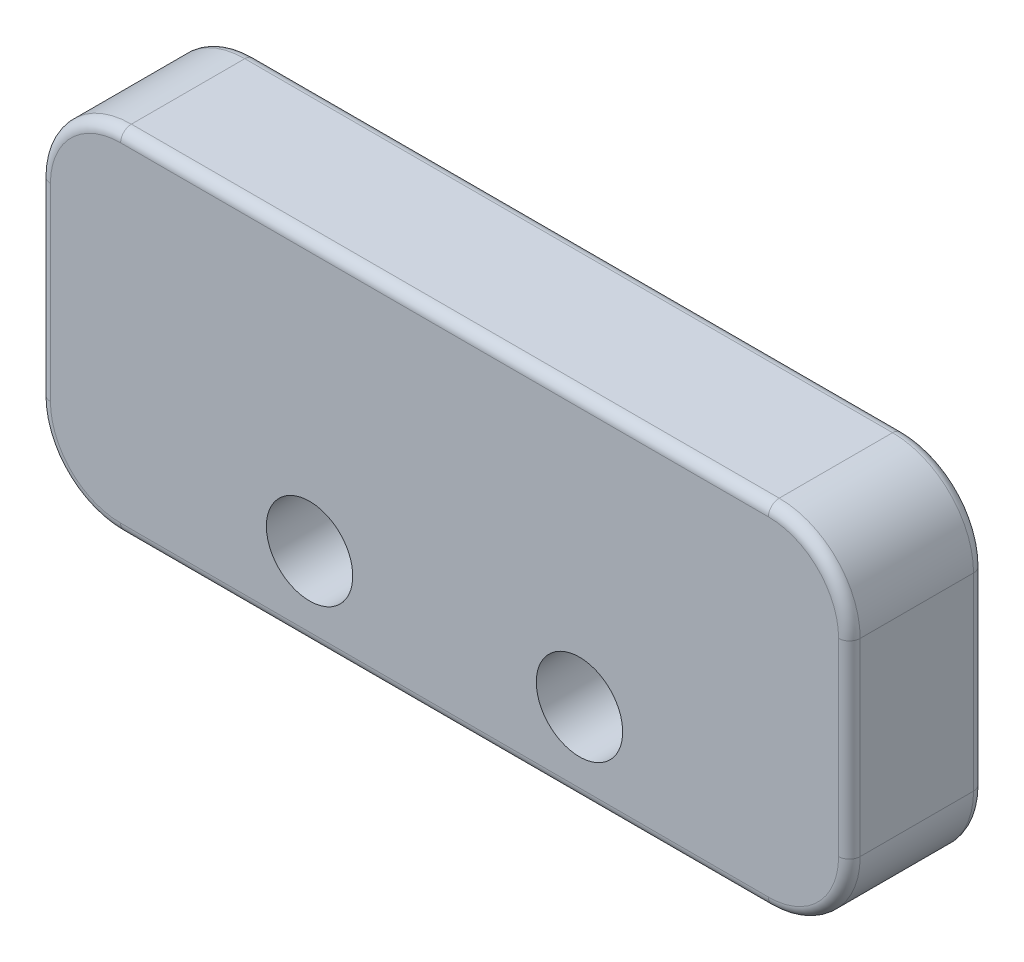
SolidWorks part; units mm, degrees
ref_plane "Front Plane" through (0, 0, 0) normal (0, 0, 1) x (1, 0, 0)
ref_plane "Top Plane" through (0, 0, 0) normal (0, 1, 0) x (1, 0, 0)
ref_plane "Right Plane" through (0, 0, 0) normal (1, 0, 0) x (0, 0, -1)
sketch "Sketch1" plane through (0, 0, 0) normal (0, 0, 1) x (1, 0, 0)
  line L1 (0, 0) -> (30, 0)
  line L2 (0, 0) -> (0, -13)
  line L3 (0, -13) -> (30, -13)
  line L4 (30, 0) -> (30, -13)
  dimension "D1" = 30
  dimension "D2" = 13
extrude "Boss-Extrude1" add sketch "Sketch1" along normal blind 5
sketch "Sketch2" plane through (0, 0, 0) normal (0, 0, -1) x (-1, 0, 0)
  line L0 (-30, 0) -> (0, 0) construction
  line L1 (-30, -13) -> (-30, 0) construction
  line L2 (0, 0) -> (0, -13) construction
  circle A0 centre (-20, -10) radius 1.6
  circle A1 centre (-10, -10) radius 1.6
  dimension "D5" = 3.2
  dimension "D6" = 3.2
  dimension "D1" = 10
  dimension "D2" = 10
  dimension "D3" = 10
  dimension "D4" = 10
extrude "Cut-Extrude1" cut sketch "Sketch2" against normal through all
fillet "Fillet1" radius 3 4 edges at (0, 0, 2.5) (0, -13, 2.5) (30, -13, 2.5) (30, 0, 2.5)
fillet "Fillet2" radius 0.4 16 edges at (29.1213, -0.8787, 5) (30, -6.5, 5) (29.1213, -12.1213, 5) (15, -13, 5) (0.8787, -12.1213, 5) (0, -6.5, 5) (0.8787, -0.8787, 5) (29.1213, -0.8787, 0) (30, -6.5, 0) (29.1213, -12.1213, 0) (15, -13, 0) (0.8787, -12.1213, 0) (0, -6.5, 0) (0.8787, -0.8787, 0) (15, 0, 5) (15, 0, 0)
equation "\"D2@Sketch1\"=20-(20-6)/2"
